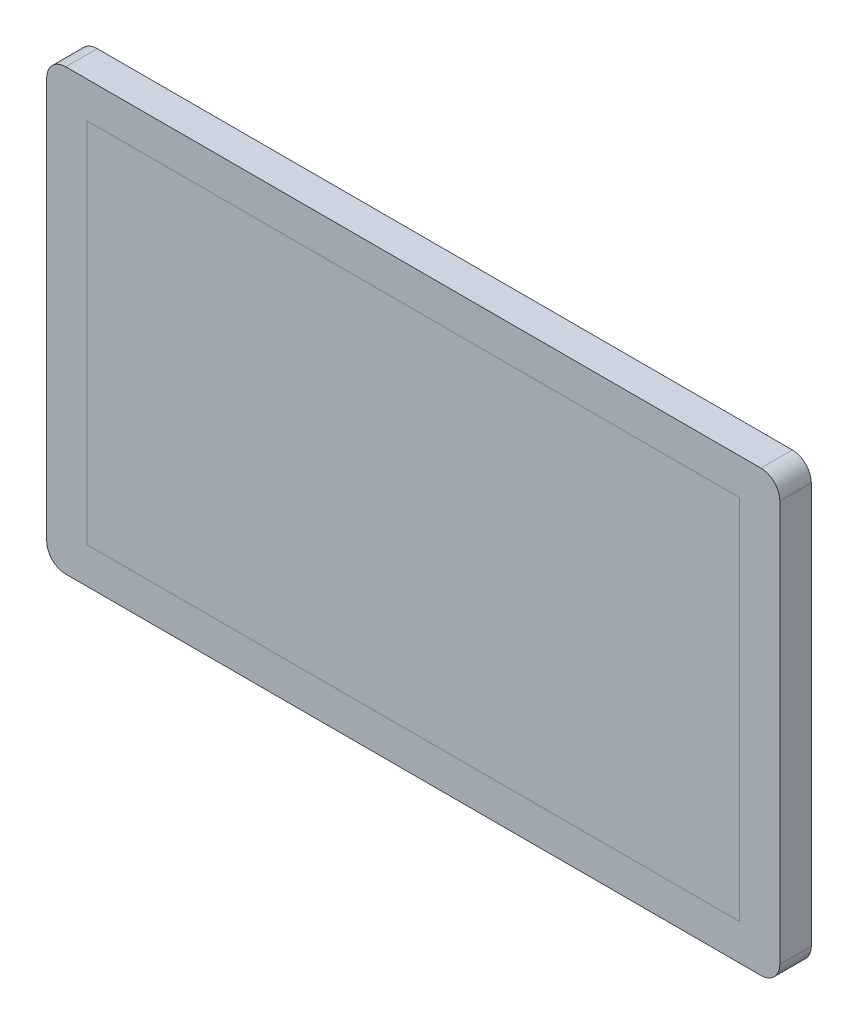
SolidWorks part; units mm, degrees
ref_plane "Front Plane" through (0, 0, 0) normal (0, 0, 1) x (1, 0, 0)
ref_plane "Top Plane" through (0, 0, 0) normal (0, 1, 0) x (1, 0, 0)
ref_plane "Right Plane" through (0, 0, 0) normal (1, 0, 0) x (0, 0, -1)
sketch "Sketch1" plane through (0, 0, 0) normal (0, 0, 1) x (1, 0, 0)
  line L1 (-183.3, 115.85) -> (183.3, 115.85)
  line L2 (-193.3, 105.85) -> (-193.3, -105.85)
  line L3 (-183.3, -115.85) -> (183.3, -115.85)
  line L4 (193.3, 105.85) -> (193.3, -105.85)
  line L5 (-193.3, 115.85) -> (193.3, -115.85) construction
  line L6 (-193.3, -115.85) -> (193.3, 115.85) construction
  arc A0 (183.3, 115.85) -> (193.3, 105.85) centre (183.3, 105.85) cw
  arc A1 (193.3, -105.85) -> (183.3, -115.85) centre (183.3, -105.85) cw
  arc A2 (-183.3, -115.85) -> (-193.3, -105.85) centre (-183.3, -105.85) cw
  arc A3 (-193.3, 105.85) -> (-183.3, 115.85) centre (-183.3, 105.85) cw
  point P0 (0, 0)
  dimension "D3" = 10
  dimension "D1" = 386.6
  dimension "D2" = 231.7
extrude "Boss-Extrude1" add sketch "Sketch1" along normal blind 16.6
sketch "Sketch2" plane through (0, 0, 16.6) normal (0, 0, 1) x (1, 0, 0)
  line L1 (-172.1, -96.8) -> (172.1, -96.8)
  line L2 (-172.1, -96.8) -> (-172.1, 96.8)
  line L3 (-172.1, 96.8) -> (172.1, 96.8)
  line L4 (172.1, -96.8) -> (172.1, 96.8)
  line L5 (-172.1, -96.8) -> (172.1, 96.8) construction
  line L6 (-172.1, 96.8) -> (172.1, -96.8) construction
  point P0 (0, 0)
  dimension "D1" = 344.2
  dimension "D2" = 193.6
split line "Split Line1"
